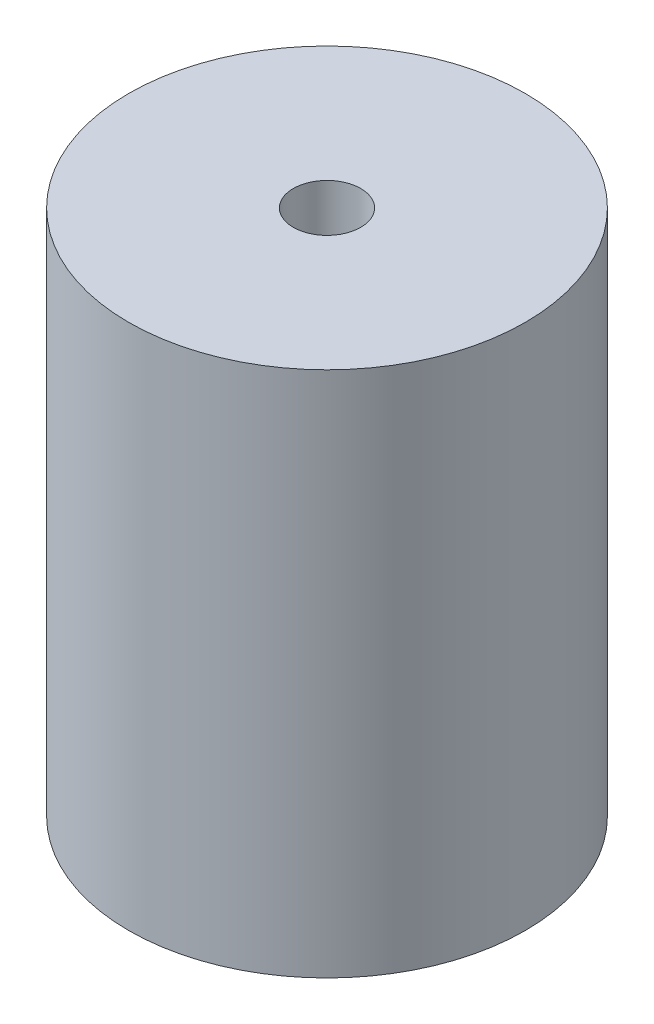
SolidWorks part; units mm, degrees
ref_plane "Alzado" through (0, 0, 0) normal (0, 0, 1) x (1, 0, 0)
ref_plane "Planta" through (0, 0, 0) normal (0, 1, 0) x (1, 0, 0)
ref_plane "Vista lateral" through (0, 0, 0) normal (1, 0, 0) x (0, 0, -1)
sketch "Croquis6" plane through (0, 0, 0) normal (0, 0, 1) x (1, 0, 0)
  line L0 (0, 0) -> (0, 48.8791) construction
  line L1 (0, 48.8791) -> (0, -50.0906) construction
  line L2 (5.1183, 43.6638) -> (30.1183, 43.6638)
  line L3 (30.1183, 43.6638) -> (30.1183, -36.3362)
  line L4 (30.1183, -36.3362) -> (5.1183, -36.3362)
  line L5 (5.1183, -36.3362) -> (5.1183, -16.3362)
  line L6 (5.1183, -16.3362) -> (20.1183, -16.3362)
  line L7 (20.1183, -16.3362) -> (20.1183, 23.6638)
  line L8 (20.1183, 23.6638) -> (5.1183, 23.6638)
  line L9 (5.1183, 23.6638) -> (5.1183, 43.6638)
revolve "Revolución2" add sketch "Croquis6" angle 360 about L0
